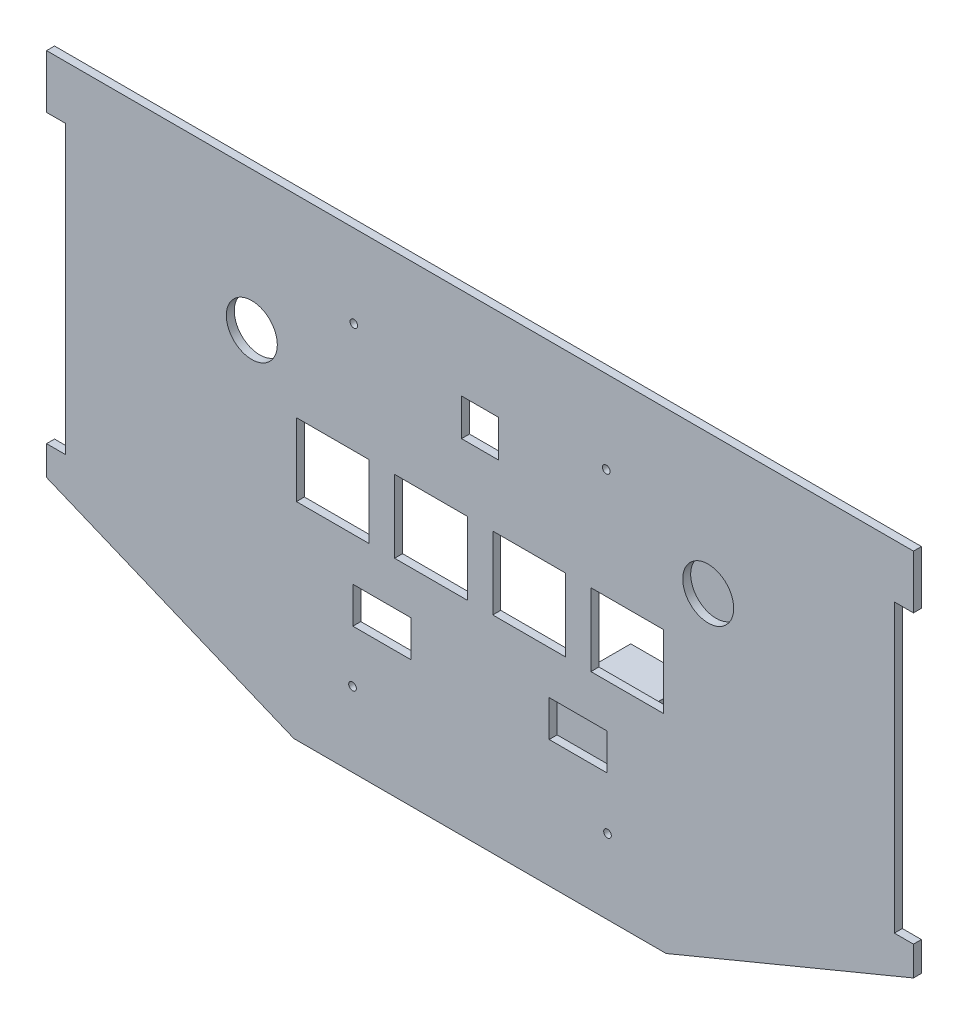
SolidWorks part; units mm, degrees
ref_plane "Front Plane" through (0, 0, 0) normal (0, 0, 1) x (1, 0, 0)
ref_plane "Top Plane" through (0, 0, 0) normal (0, 1, 0) x (1, 0, 0)
ref_plane "Right Plane" through (0, 0, 0) normal (1, 0, 0) x (0, 0, -1)
sketch "Sketch1" plane through (0, 0, 0) normal (0, 0, 1) x (1, 0, 0)
  line L0 (-340, 0) -> (340, 0)
  line L1 (340, 0) -> (340, -42)
  line L2 (340, -42) -> (325, -42)
  line L3 (325, -42) -> (325, -267)
  line L4 (325, -267) -> (340, -267)
  line L5 (340, -267) -> (340, -290)
  line L6 (340, -290) -> (145.9853, -370.3635)
  line L7 (145.9853, -370.3635) -> (-145.9853, -370.3635)
  line L8 (-145.9853, -370.3635) -> (-340, -290)
  line L9 (-340, -290) -> (-340, -267)
  line L10 (-340, -267) -> (-325, -267)
  line L11 (-325, -267) -> (-325, -42)
  line L12 (-325, -42) -> (-340, -42)
  line L13 (-340, -42) -> (-340, 0)
  line L14 (-144, -151.3635) -> (-87, -151.3635)
  line L15 (-87, -151.3635) -> (-87, -208.3635)
  line L16 (-87, -208.3635) -> (-144, -208.3635)
  line L17 (-144, -208.3635) -> (-144, -151.3635)
  line L18 (-10, -208.3635) -> (-67, -208.3635)
  line L19 (-67, -208.3635) -> (-67, -151.3635)
  line L20 (-67, -151.3635) -> (-10, -151.3635)
  line L21 (-10, -151.3635) -> (-10, -208.3635)
  line L22 (67, -208.3635) -> (10, -208.3635)
  line L23 (10, -208.3635) -> (10, -151.3635)
  line L24 (10, -151.3635) -> (67, -151.3635)
  line L25 (67, -151.3635) -> (67, -208.3635)
  line L26 (144, -208.3635) -> (87, -208.3635)
  line L27 (87, -208.3635) -> (87, -151.3635)
  line L28 (87, -151.3635) -> (144, -151.3635)
  line L29 (144, -151.3635) -> (144, -208.3635)
  line L30 (-87, -179.8635) -> (-67, -179.8635)
  line L31 (-10, -179.8635) -> (10, -179.8635)
  line L32 (67, -179.8635) -> (87, -179.8635)
  line L33 (-99.75, -242.3635) -> (-54.25, -242.3635)
  line L34 (-54.25, -242.3635) -> (-54.25, -270.8635)
  line L35 (-54.25, -270.8635) -> (-99.75, -270.8635)
  line L36 (-99.75, -270.8635) -> (-99.75, -242.3635)
  line L37 (99.75, -270.8635) -> (54.25, -270.8635)
  line L38 (54.25, -270.8635) -> (54.25, -242.3635)
  line L39 (54.25, -242.3635) -> (99.75, -242.3635)
  line L40 (99.75, -242.3635) -> (99.75, -270.8635)
  line L41 (-77, -179.8635) -> (-77, -242.3635)
  line L42 (77, -179.8635) -> (77, -242.3635)
  line L43 (0, -179.8635) -> (0, -370.3635)
  line L44 (-14.5, -71.8635) -> (14.5, -71.8635)
  line L45 (14.5, -71.8635) -> (14.5, -100.8635)
  line L46 (14.5, -100.8635) -> (-14.5, -100.8635)
  line L47 (-14.5, -100.8635) -> (-14.5, -71.8635)
  line L48 (0, -100.8635) -> (0, -179.8635)
  line L49 (-179, -129.3635) -> (-179, -151.3635)
  line L50 (-159, -109.3635) -> (-144, -109.3635)
  circle A0 centre (-179, -109.3635) radius 16.25
  circle A1 centre (-179, -109.3635) radius 20
  circle A2 centre (179, -109.3635) radius 20
  circle A3 centre (179, -109.3635) radius 16.25
  circle A4 centre (-99, -65) radius 3
  circle A5 centre (-100, -311.8635) radius 3
  circle A6 centre (99, -65) radius 3
  circle A7 centre (100, -311.8635) radius 3
extrude "Boss-Extrude1" add sketch "Sketch1" along normal blind 6.25
sketch "Sketch2" plane through (0, 0, 0) normal (0, 0, 1) x (1, 0, 0)
  line L0 (99.75, -270.8635) -> (54.25, -270.8635) construction
  line L1 (214.25, -88.1135) -> (143.75, -88.1135)
  line L2 (214.25, -88.1135) -> (214.25, -130.6135)
  line L3 (214.25, -130.6135) -> (143.75, -130.6135)
  line L4 (143.75, -88.1135) -> (143.75, -130.6135)
  line L5 (102, -240.1135) -> (52, -240.1135)
  line L6 (102, -240.1135) -> (102, -273.1135)
  line L7 (102, -273.1135) -> (52, -273.1135)
  line L8 (52, -240.1135) -> (52, -273.1135)
  line L9 (99.75, -242.3635) -> (99.75, -270.8635) construction
  point P4 (214.25, -109.3635)
  point P6 (179, -88.1135)
  point P11 (77, -273.1135)
  point P14 (77, -270.8635)
  point P15 (102, -256.6135)
  point P18 (99.75, -256.6135)
  dimension "D1" = 70.5
  dimension "D2" = 42.5
  dimension "D3" = 33
  dimension "D4" = 50
extrude "Boss-Extrude2" add sketch "Sketch2" against normal blind 60
